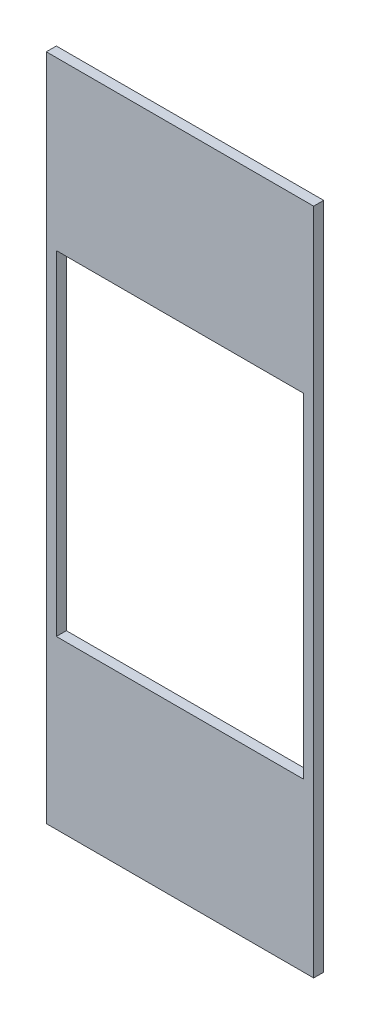
SolidWorks part; units mm, degrees
ref_plane "Front Plane" through (0, 0, 0) normal (0, 0, 1) x (1, 0, 0)
ref_plane "Top Plane" through (0, 0, 0) normal (0, 1, 0) x (1, 0, 0)
ref_plane "Right Plane" through (0, 0, 0) normal (1, 0, 0) x (0, 0, -1)
sketch "Sketch1" plane through (0, 0, 0) normal (0, 0, 1) x (1, 0, 0)
  line L0 (-20, 50) -> (20, 50)
  line L2 (-20, 50) -> (-20, -50)
  line L3 (-20, -50) -> (20, -50)
  line L4 (20, -50) -> (20, 50)
extrude "Boss-Extrude1" add sketch "Sketch1" along normal blind 1.5
sketch "Sketch2" plane through (0, 0, 1.5) normal (0, 0, 1) x (1, 0, 0)
  line L0 (-18.5, 25) -> (-18.5, -25)
  line L1 (-18.5, -25) -> (18.5, -25)
  line L2 (-18.5, 25) -> (18.5, 25)
  line L3 (18.5, 25) -> (18.5, -25)
extrude "Cut-Extrude1" cut sketch "Sketch2" against normal blind 1.5
